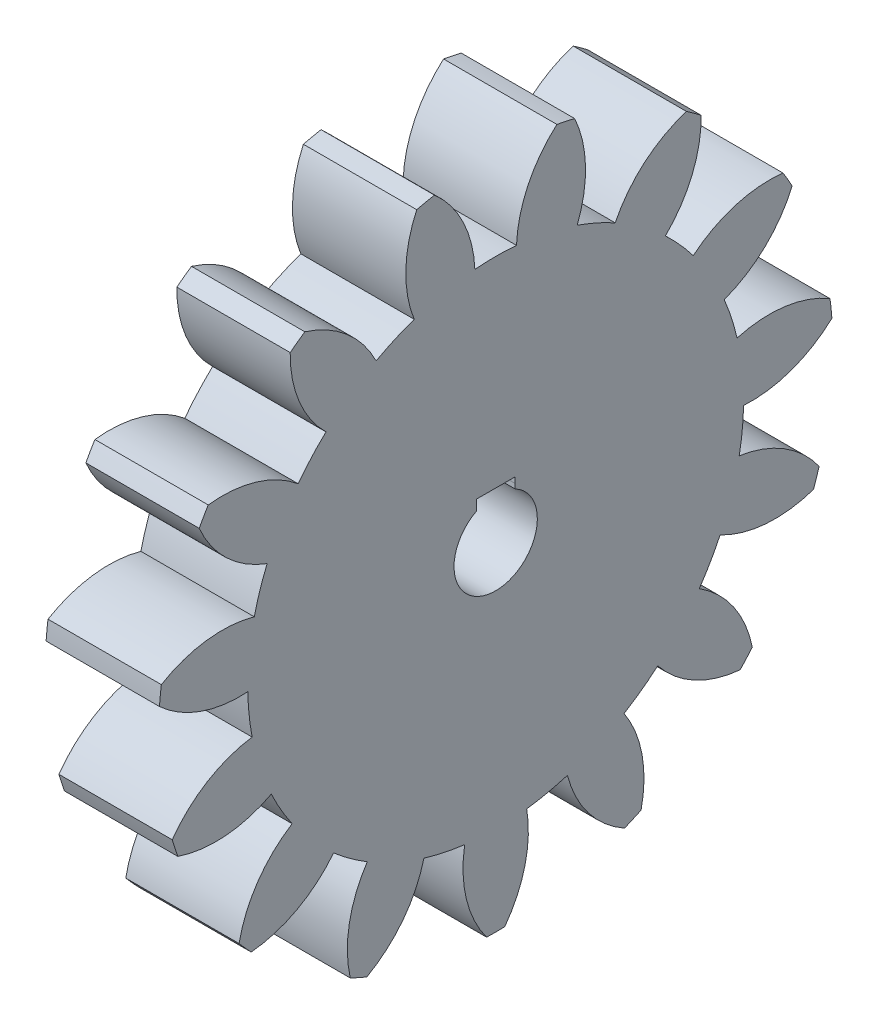
SolidWorks part; units mm, degrees
ref_plane "Plane1" through (0, 0, 0) normal (0, 0, 1) x (1, 0, 0)
ref_plane "Plane2" through (0, 0, 0) normal (0, 1, 0) x (1, 0, 0)
ref_plane "Plane3" through (0, 0, 0) normal (1, 0, 0) x (0, 0, -1)
sketch "HoldingSke" plane through (0, 0, 0) normal (0, 1, 0) x (1, 0, 0)
  line L0 (0, 0) -> (0.276, -0.0739)
  line L1 (-15, 0) -> (100, 0) construction
  line L2 (0, 0) -> (-2.1039, 2.3779)
  line L3 (0, 0) -> (-11.863, 4.5341)
  line L4 (0, 0) -> (8.3417, 2.2352)
  line L5 (0, 0) -> (-46.8476, -17.4728)
  line L6 (0, 0) -> (-8.2896, -5.593)
  line L7 (-2.1039, 2.3779) -> (8.6586, 51.2059)
  line L8 (-76.2, 54.61) -> (-75.2, 54.61)
  line L9 (-71.009, 38.7566) -> (-53.1078, 45.2721)
  line L10 (-76.2, 71.12) -> (104.1128, 71.12)
  line L11 (0, 0) -> (-10, 0)
  line L12 (-76.2, 101.6) -> (-76.083, 101.6)
  line L13 (24.9733, 27.94) -> (52.9518, 28.4284)
  line L14 (24.9733, 27.94) -> (24.9743, 27.94)
  line L15 (24.9733, 27.94) -> (100.4006, 29.5858)
  line L16 (-63.627, -3.5) -> (-12.827, -3.5)
  circle A0 centre (0, 0) radius 3.5
  circle A1 centre (0, 0) radius 21.874
  circle A2 centre (0, 0) radius 37.5
  circle A3 centre (0, 0) radius 3.5
  dimension "MHD" = 43.748
  dimension "Hub_dia" = 75
  dimension "Bore" = 7
  dimension "MBD" = 7
  dimension "Num_teeth" = 15
  dimension "Pitch_radius" = 180.3128
  dimension "Pitch" = 0.2857
  dimension "Width" = 10
  dimension "Overall_len" = 50
  dimension "Show_teeth" = 15
  dimension "Thickness" = 10
  dimension "OAL" = 50.0001
  dimension "T_dim" = 1
  dimension "Ap" = 20
  dimension "H" = 19.05
  dimension "Backlash" = 0.117
  dimension "Addendum_fac" = 1
  dimension "Dedendum_fac" = 1.25
  dimension "Clearance_fac" = 0.25
  dimension "Dedendum_add" = 0.001
  dimension "Module" = 3.5
sketch "BasProSke" plane through (0, 0, 0) normal (0, 1, 0) x (1, 0, 0)
  line L0 (-10, 0) -> (60, 0) construction
  line L1 (0, 0) -> (0, 29.75)
  line L2 (0, 0) -> (10, 0)
  line L3 (10, 0) -> (10, 29.75)
  line L4 (10, 29.75) -> (0, 29.75)
  dimension "Diameter" = 59.5
  dimension "Thickness" = 10
revolve "Base-Revolve" add sketch "BasProSke" angle 360 about L0
sketch "TooCutSke" plane through (0, 0, 0) normal (1, 0, 0) x (0, 0, -1)
  line L1 (0, 0) -> (0, 107) construction
  line L2 (0, 0) -> (-2.9485, 26.0839) construction
  line L3 (0, 0) -> (-10.8642, 51.1119) construction
  line L4 (-2.9485, 26.0839) -> (-5.4321, 25.556) construction
  arc A0 (1.8373, 21.7967) -> (-1.8373, 21.7967) centre (0, 0) ccw
  arc A1 (5.4253, 29.277) -> (-5.4253, 29.277) centre (0, 0) ccw
  circle A2 centre (0, 0) radius 26.25 construction
  circle A3 centre (0, 0) radius 24.6669 construction
  arc A4 (-1.8373, 21.7967) -> (-5.4253, 29.277) centre (-12.3284, 21.3651) ccw
  arc A5 (5.4253, 29.277) -> (1.8373, 21.7967) centre (12.3284, 21.3651) ccw
  dimension "Root_dia" = 43.748
  dimension "Overcut_dia" = 59.5508
  dimension "Pitch_dia" = 52.5
  dimension "Base_dia" = 49.3339
  dimension "Flank_rad" = 10.5
  dimension "Half_ang" = 12
  dimension "Half_CT" = 2.5391
extrude "ToothCut" cut sketch "TooCutSke" along normal through all
fillet "Breaks" [suppressed] radius 0.07
fillet "RootFillets" [suppressed] radius 0.876
pattern_circular "TeethCuts" count 15 every 24 about axis through (-10, 0, 0) along (1, 0, 0) of "ToothCut", "RootFillets", "Breaks"
sketch "HubNeaOneSke" plane through (0, 0, 0) normal (-1, 0, 0) x (0, 0, 1)
  circle A0 centre (0, 0) radius 21.874
  dimension "Diameter" = 43.748
extrude "HubNearOne" [suppressed] add sketch "HubNeaOneSke" along normal blind 40.0001
sketch "HubNeaBotSke" plane through (0, 0, 0) normal (-1, 0, 0) x (0, 0, 1)
  circle A0 centre (0, 0) radius 21.874
  dimension "Diameter" = 43.748
extrude "HubNearBoth" [suppressed] add sketch "HubNeaBotSke" along normal blind 20
ref_plane "FarPln" through (10, 0, 0) normal (1, 0, 0) x (0, 0, -1)
sketch "HubFarSke" plane through (10, 0, 0) normal (1, 0, 0) x (0, 0, -1)
  circle A0 centre (0, 0) radius 21.874
  dimension "Diameter" = 43.748
extrude "HubFar" [suppressed] add sketch "HubFarSke" along normal blind 20
sketch "BorSke" plane through (0, 0, 0) normal (1, 0, 0) x (0, 0, -1)
  circle A0 centre (0, 0) radius 3.5
  dimension "Diameter" = 7
extrude "Bore" cut sketch "BorSke" along normal mid plane 100.0001
sketch "KeySke" plane through (0, 0, 0) normal (1, 0, 0) x (0, 0, -1)
  line L0 (-1, 0) -> (-1, 4.5)
  line L1 (-1, 4.5) -> (1, 4.5)
  line L2 (1, 4.5) -> (1, 0)
  line L3 (0, 0) -> (0, 34) construction
  line L4 (-1, 0) -> (1, 0)
  dimension "Offset" = 4.5
  dimension "Width" = 2
extrude "Keyway" [suppressed] cut sketch "KeySke" along normal mid plane 100.0001
pattern_circular "Keyway2" [suppressed] count 2 every 90 about axis through (-10, 0, 0) along (1, 0, 0)
sketch "Sketch1" plane through (10, 0, 0) normal (1, 0, 0) x (0, 0, -1)
  circle A0 centre (0, 0) radius 3.675
  dimension "D1" = 7.35
extrude "Cut-Extrude1" cut sketch "Sketch1" against normal blind 10
sketch "Sketch2" plane through (10, 0, 0) normal (1, 0, 0) x (0, 0, -1)
  line L0 (0, 0) -> (0, 3.675) construction
  line L2 (1.71, 3.675) -> (1.71, 4.175)
  line L3 (1.71, 4.175) -> (-1.71, 4.175)
  line L4 (-1.71, 4.175) -> (-1.71, 3.675)
  line L6 (-1.71, 3.675) -> (-1.71, 3.2529)
  line L7 (-1.71, 3.2529) -> (0, 3.675)
  line L8 (1.71, 3.2529) -> (1.71, 3.675)
  circle A0 centre (0, 0) radius 3.675 construction
  dimension "D1" = 1.71
  dimension "D2" = 1.71
  dimension "D3" = 0.5
extrude "Cut-Extrude2" cut sketch "Sketch2" against normal through all and the other way through all
equation "' \"Module@HoldingSke\" = 6.35"
equation "' \"Num_teeth@HoldingSke\" = 12"
equation "' \"Ap@HoldingSke\" =  20"
equation "' \"Width@HoldingSke\" = 0.5 * 25.4"
equation "' \"Hub_dia@HoldingSke\"= 1 * 25.4"
equation "' \"Overall_len@HoldingSke\" = 1.0 * 25.4"
equation "' \"Bore@HoldingSke\" = 0.75 * 25.4"
equation "' \"T_dim@HoldingSke\" = 0.1 * 25.4"
equation "' \"Width@KeySke\" = 0.25 * 25.4"
equation "' \"Show_teeth@HoldingSke\" = 13"
equation "' \"Backlash@HoldingSke\" = 0.009 * 25.4"
equation "' \"Addendum_fac@HoldingSke\" = 1.0"
equation "' \"Dedendum_fac@HoldingSke\" = 1.25"
equation "' \"Dedendum_add@HoldingSke\" = 0.00005 * 25.4"
equation "' \"Clearance_fac@HoldingSke\" = 0.25"
equation "\"Pitch@HoldingSke\" = 1 / \"Module@HoldingSke\""
equation "\"Overcut_dia@TooCutSke\" = (\"Num_teeth@HoldingSke\" + 2 * \"Addendum_fac@HoldingSke\") / \"Pitch@HoldingSke\" + 0.002 * 25.4"
equation "\"Pitch_dia@TooCutSke\" = \"Num_teeth@HoldingSke\" / \"Pitch@HoldingSke\""
equation "\"Base_dia@TooCutSke\" = \"Num_teeth@HoldingSke\" / \"Pitch@HoldingSke\" * cos((\"Ap@HoldingSke\"  * 3.14159265 / 180))"
equation "\"Root_dia@TooCutSke\" = (\"Num_teeth@HoldingSke\" + 2) / \"Pitch@HoldingSke\" - 2 * (\"Addendum_fac@HoldingSke\" + \"Dedendum_fac@HoldingSke\") / \"Pitch@HoldingSke\" - \"Dedendum_add@HoldingSke\" * 2"
equation "\"Half_ang@TooCutSke\" = 180 / \"Num_teeth@HoldingSke\""
equation "\"Half_CT@TooCutSke\" = \"Num_teeth@HoldingSke\" / \"Pitch@HoldingSke\" * sin((3.14159265 / 2 / \"Num_teeth@HoldingSke\")) / 2 - 7 * \"Backlash@HoldingSke\" / 4"
equation "\"Flank_rad@TooCutSke\" = \"Num_teeth@HoldingSke\" / \"Pitch@HoldingSke\" / 5"
equation "\"Radius@RootFillets\" = \"Clearance_fac@HoldingSke\" / \"Pitch@HoldingSke\" + \"Dedendum_add@HoldingSke\""
equation "\"Break_rad@Breaks\" = 0.02 / \"Pitch@HoldingSke\""
equation "\"Thickness@HoldingSke\" = \"Width@HoldingSke\""
equation "\"OAL@HoldingSke\" = \"Thickness@HoldingSke\""
equation "\"MHD@HoldingSke\" = (\"Num_teeth@HoldingSke\" + 2) / \"Pitch@HoldingSke\" - 2 * (\"Addendum_fac@HoldingSke\" + \"Dedendum_fac@HoldingSke\")  / \"Pitch@HoldingSke\" - \"Dedendum_add@HoldingSke\" * 2"
equation "\"MBD@HoldingSke\" = (\"Num_teeth@HoldingSke\" + 2) / \"Pitch@HoldingSke\" - 2 * (\"Addendum_fac@HoldingSke\" + \"Dedendum_fac@HoldingSke\")  / \"Pitch@HoldingSke\" - \"Dedendum_add@HoldingSke\" * 2 - 0.002 * 25.4"
equation "\"MHD@HoldingSke\" = ((sgn( \"MHD@HoldingSke\" - \"Hub_dia@HoldingSke\" )-1)*( \"MHD@HoldingSke\" - \"Hub_dia@HoldingSke\" ))/-2+ \"Hub_dia@HoldingSke\""
equation "\"MBD@HoldingSke\" = ((sgn( \"MBD@HoldingSke\" - \"Bore@HoldingSke\" )-1)*( \"MBD@HoldingSke\" - \"Bore@HoldingSke\" ))/-2+ \"Bore@HoldingSke\""
equation "\"OAL@HoldingSke\" = ((sgn( \"OAL@HoldingSke\" - \"Overall_len@HoldingSke\" )+1)*( \"OAL@HoldingSke\" - \"Overall_len@HoldingSke\" ))/2 + \"Overall_len@HoldingSke\" + 0.000002 * 25.4"
equation "\"Num_teeth@TeethCuts\" = int( \"Show_teeth@HoldingSke\" ) + 1"
equation "\"Num_teeth@TeethCuts\" = ((sgn( \"Num_teeth@TeethCuts\" - \"Num_teeth@HoldingSke\" )-1)*( \"Num_teeth@TeethCuts\" - \"Num_teeth@HoldingSke\" ))/-2+ \"Num_teeth@HoldingSke\""
equation "\"Num_teeth@TeethCuts\" = ((sgn( \"Num_teeth@TeethCuts\" - 2.0)+1)*( \"Num_teeth@TeethCuts\" - 2.0))/2 +2.0"
equation "\"Angle@TeethCuts\" = 360.0 / \"Num_teeth@HoldingSke\""
equation "\"Diameter@BasProSke\" = (\"Num_teeth@HoldingSke\" + 2 * \"Addendum_fac@HoldingSke\") / \"Pitch@HoldingSke\""
equation "\"Thickness@BasProSke\"  = \"Thickness@HoldingSke\""
equation "' \"Fillet_rad@BasProSke\" =  \"Thickness@HoldingSke\" * 0.05"
equation "\"MHD@HoldingSke\" = ((sgn( \"MHD@HoldingSke\" - \"Root_dia@TooCutSke\" )-1)*( \"MHD@HoldingSke\" - \"Root_dia@TooCutSke\" ))/-2+ \"Root_dia@TooCutSke\""
equation "\"Diameter@HubNeaOneSke\" = \"MHD@HoldingSke\""
equation "\"Length@HubNearOne\" = \"OAL@HoldingSke\" - \"Thickness@BasProSke\""
equation "\"Diameter@HubNeaBotSke\" = \"MHD@HoldingSke\""
equation "\"Length@HubNearBoth\" = ( \"OAL@HoldingSke\" - \"Thickness@BasProSke\" ) / 2.0"
equation "\"Thickness@FarPln\" = \"Thickness@BasProSke\""
equation "\"Diameter@HubFarSke\" = \"MHD@HoldingSke\""
equation "\"Length@HubFar\" = ( \"OAL@HoldingSke\" - \"Thickness@BasProSke\" ) / 2.0"
equation "\"Diameter@BorSke\" = \"MBD@HoldingSke\""
equation "\"D1@Bore\" = \"OAL@HoldingSke\" * 2.0"
equation "\"D1@Keyway\" = \"OAL@HoldingSke\" * 2.0"
equation "\"Offset@KeySke\" = \"T_dim@HoldingSke\" + \"MBD@HoldingSke\" / 2.0"
